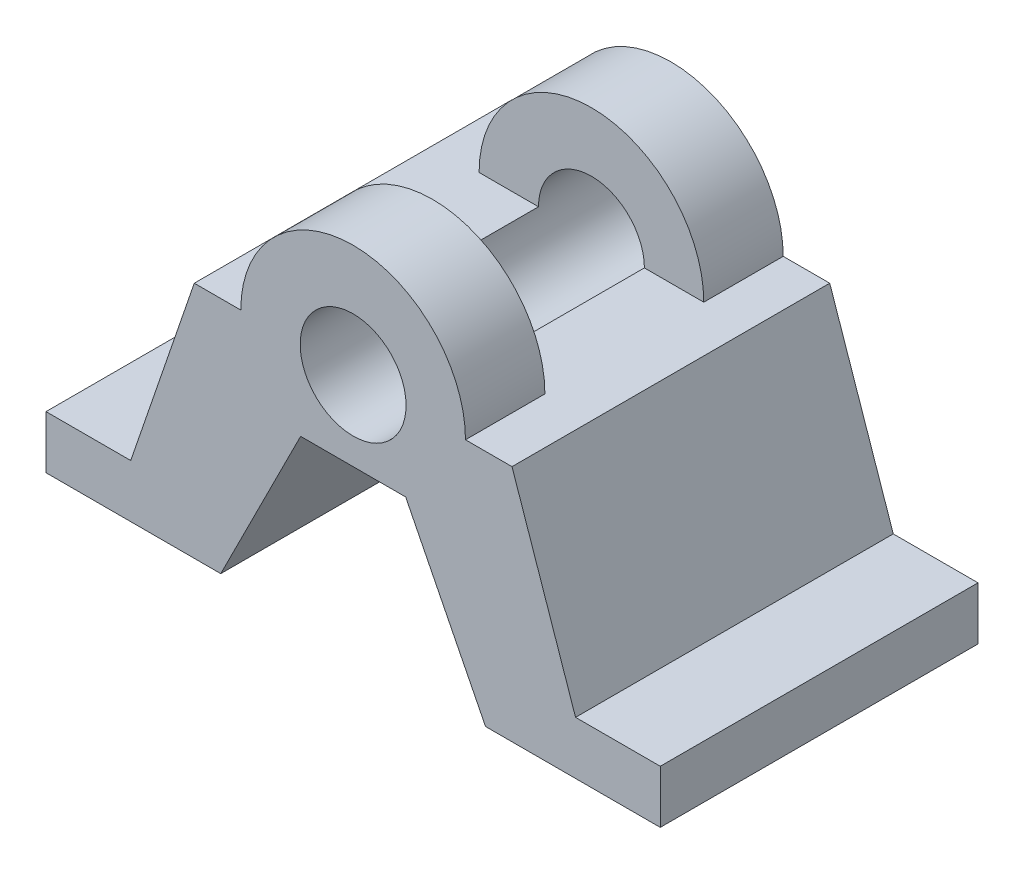
SolidWorks part; units mm, degrees
ref_plane "Front Plane" through (0, 0, 0) normal (0, 0, 1) x (1, 0, 0)
ref_plane "Top Plane" through (0, 0, 0) normal (0, 1, 0) x (1, 0, 0)
ref_plane "Right Plane" through (0, 0, 0) normal (1, 0, 0) x (0, 0, -1)
sketch "Sketch1" plane through (0, 0, 0) normal (0, 0, 1) x (1, 0, 0)
  line L0 (-58, 0) -> (-58, 10)
  line L1 (-58, 10) -> (-42, 10)
  line L2 (-42, 10) -> (-30, 45)
  line L4 (-58, 0) -> (-25, 0)
  line L7 (42, 10) -> (30, 45)
  line L8 (-25, 0) -> (-9.9173, 30)
  line L9 (-9.9173, 30) -> (9.9173, 30)
  line L10 (-30, 45) -> (30, 45)
  line L11 (25, 0) -> (9.9173, 30)
  line L13 (25, 0) -> (58, 0)
  line L14 (58, 10) -> (58, 0)
  line L15 (58, 10) -> (42, 10)
  point P2 (0, 30)
  point P5 (0, 45)
  dimension "D1" = 10
  dimension "D2" = 30
  dimension "D3" = 16
  dimension "D4" = 16
  dimension "D5" = 60
  dimension "D6" = 33
  dimension "D7" = 45
  dimension "D8" = 116
  dimension "D10" = 33
  dimension "D11" = 25
extrude "Boss-Extrude1" add sketch "Sketch1" against normal blind 60
sketch "Sketch2" plane through (0, 0, 0) normal (0, 0, 1) x (1, 0, 0)
  line L0 (30, 45) -> (-30, 45) construction
  line L1 (-18.0629, 33.8741) -> (18.0629, 33.8741)
  arc A0 (18.0629, 33.8741) -> (-18.0629, 33.8741) centre (0, 45) ccw
extrude "Boss-Extrude2" add sketch "Sketch2" against normal blind 15
sketch "Sketch5" plane through (0, 0, 0) normal (0, 0, 1) x (1, 0, 0)
  circle A0 centre (0, 45) radius 10
  dimension "D1" = 20
extrude "Cut-Extrude1" cut sketch "Sketch5" against normal through all
ref_plane "Plane2" through (0, 0, -30) normal (0, 0, 1) x (1, 0, 0)
mirror "Mirror1" about plane through (0, 0, -30) normal (0, 0, 1) of "Cut-Extrude1", "Boss-Extrude2"
